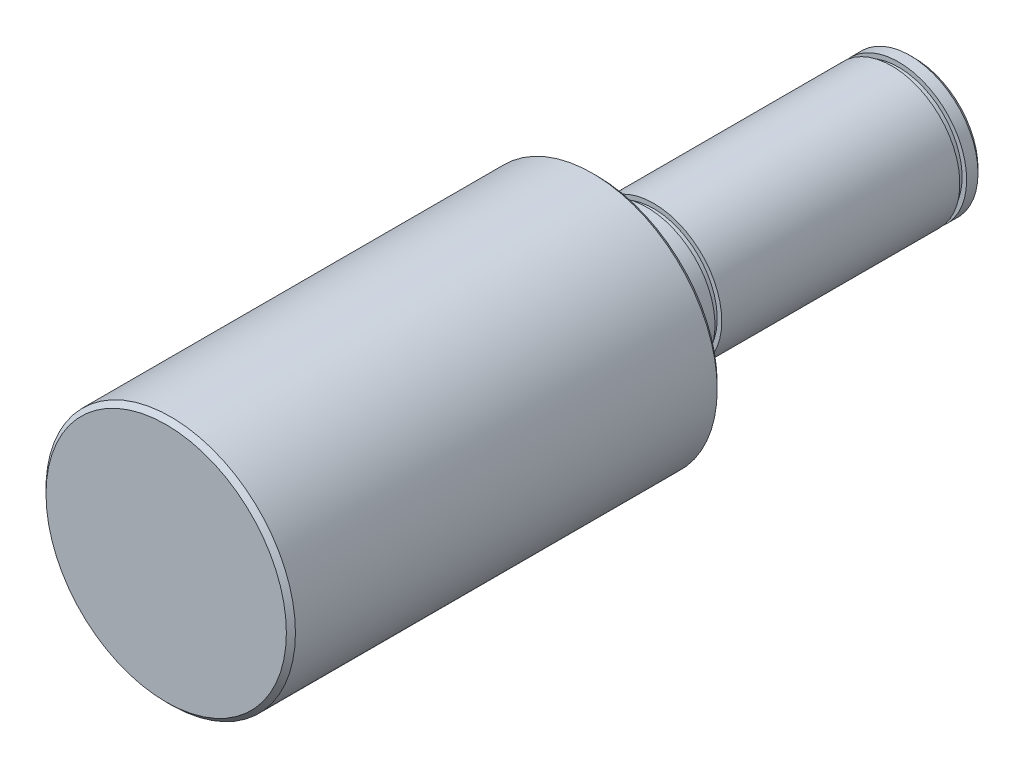
SolidWorks part; units mm, degrees
ref_plane "前视基准面" through (0, 0, 0) normal (0, 0, 1) x (1, 0, 0)
ref_plane "上视基准面" through (0, 0, 0) normal (0, 1, 0) x (1, 0, 0)
ref_plane "右视基准面" through (0, 0, 0) normal (1, 0, 0) x (0, 0, -1)
sketch "草图1" plane through (0, 0, 0) normal (0, 0, 1) x (1, 0, 0)
  circle A0 centre (0, 0) radius 15
  dimension "D1" = 30
extrude "凸台-拉伸1" add sketch "草图1" along normal blind 70
sketch "草图2" plane through (0, 0, 70) normal (0, 0, 1) x (1, 0, 0)
  circle A0 centre (0, 0) radius 27.5
  dimension "D1" = 55
extrude "凸台-拉伸2" add sketch "草图2" along normal blind 95
chamfer "倒角1" distance 1 angle 45 3 edges at (27.5, 0, 165) (27.5, 0, 70) (15, 0, 0)
sketch "草图3" plane through (0, 0, 0) normal (0, 1, 0) x (1, 0, 0)
  line L0 (0, 18.215) -> (0, -91.5401) construction
  line L1 (26.5, -70) -> (-26.5, -70) construction
  line L2 (14, -57.5) -> (19.2138, -57.5)
  line L3 (14, -57.5) -> (14, -59)
  line L4 (14, -59) -> (19.2138, -59)
  line L5 (19.2138, -57.5) -> (19.2138, -59)
  line L6 (14, -3.5) -> (19.2138, -3.5)
  line L7 (14, -3.5) -> (14, -5)
  line L8 (14, -5) -> (19.2138, -5)
  line L9 (19.2138, -3.5) -> (19.2138, -5)
  line L11 (14, 0) -> (-14, 0) construction
  dimension "D1" = 1.5
  dimension "D2" = 1.5
  dimension "D3" = 14
  dimension "D4" = 11
  dimension "D5" = 3.5
revolve "切除-旋转1" cut sketch "草图3" angle 360 about L0
